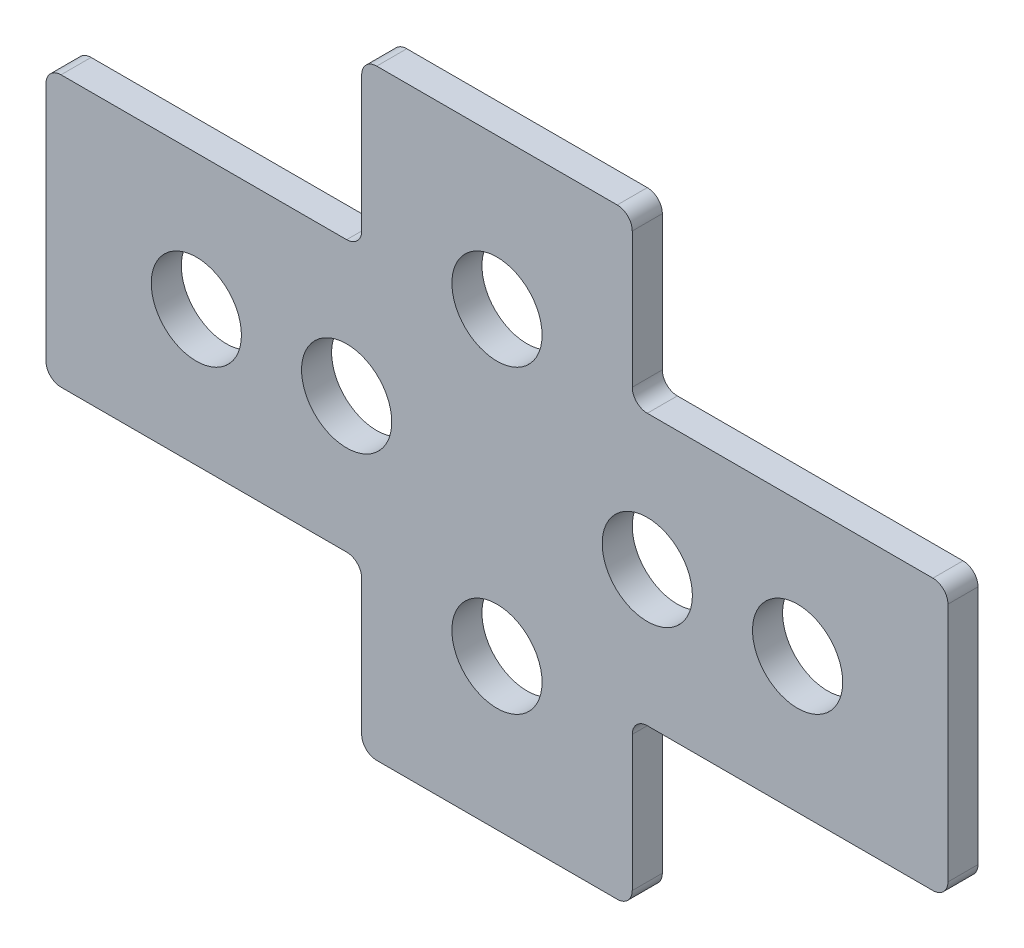
SolidWorks part; units mm, degrees
ref_plane "前视基准面" through (0, 0, 0) normal (0, 0, 1) x (1, 0, 0)
ref_plane "上视基准面" through (0, 0, 0) normal (0, 1, 0) x (1, 0, 0)
ref_plane "右视基准面" through (0, 0, 0) normal (1, 0, 0) x (0, 0, -1)
sketch "草图1" plane through (0, 0, 0) normal (0, 0, 1) x (1, 0, 0)
  line B0 (-9, -9) -> (-9, 0)
  line B1 (-9, 20) -> (-9, 29)
  line B2 (9, -9) -> (9, 0)
  line B3 (9, 20) -> (9, 29)
  line B4 (8, 30) -> (-8, 30)
  line B5 (-8, -10) -> (8, -10)
  line B6 (-30, 2) -> (-30, 18)
  line B7 (30, 18) -> (30, 2)
  line B8 (-29, 19) -> (-10, 19)
  line B9 (10, 19) -> (29, 19)
  line B10 (-29, 1) -> (-10, 1)
  line B11 (10, 1) -> (29, 1)
  arc B12 (10, 1) -> (9, 0) centre (10, 0) ccw
  arc B13 (9, 20) -> (10, 19) centre (10, 20) ccw
  arc B14 (-9, -9) -> (-8, -10) centre (-8, -9) ccw
  arc B15 (8, -10) -> (9, -9) centre (8, -9) ccw
  arc B16 (9, 29) -> (8, 30) centre (8, 29) ccw
  arc B17 (-8, 30) -> (-9, 29) centre (-8, 29) ccw
  arc B18 (-10, 19) -> (-9, 20) centre (-10, 20) ccw
  arc B19 (-9, 0) -> (-10, 1) centre (-10, 0) ccw
  arc B20 (-30, 2) -> (-29, 1) centre (-29, 2) ccw
  arc B21 (-29, 19) -> (-30, 18) centre (-29, 18) ccw
  arc B22 (30, 18) -> (29, 19) centre (29, 18) ccw
  arc B23 (29, 1) -> (30, 2) centre (29, 2) ccw
  circle B24 centre (0, 20) radius 3
  circle B25 centre (0, 0) radius 3
  circle B26 centre (-20, 10) radius 3
  circle B27 centre (-10, 10) radius 3
  circle B28 centre (20, 10) radius 3
  circle B29 centre (10, 10) radius 3
sketch_block_instance "A$C1DB30388-1"
sketch_block "A$C1DB30388"
extrude "凸台-拉伸1" add sketch "草图1" along normal blind 2
